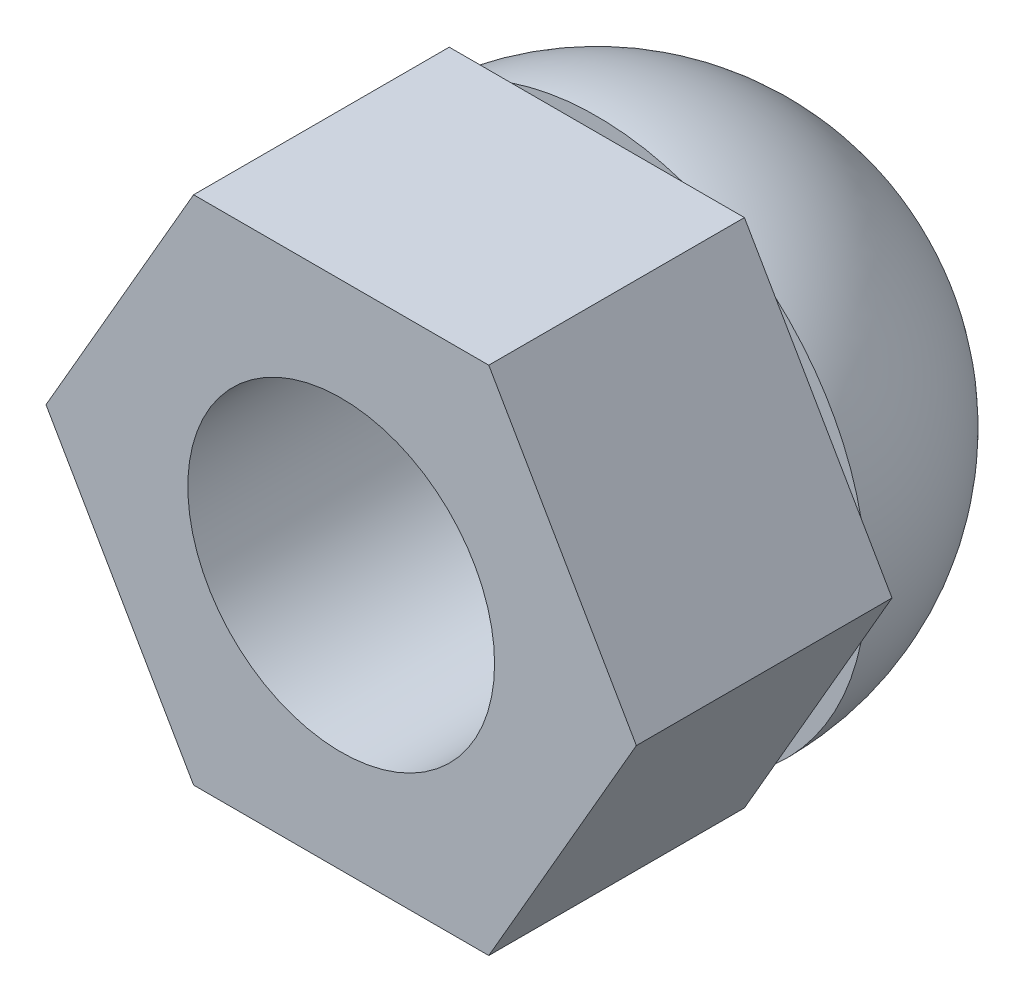
SolidWorks part; units mm, degrees
ref_plane "Plano frontal" through (0, 0, 0) normal (0, 0, 1) x (1, 0, 0)
ref_plane "Plano superior" through (0, 0, 0) normal (0, 1, 0) x (1, 0, 0)
ref_plane "Plano direito" through (0, 0, 0) normal (1, 0, 0) x (0, 0, -1)
sketch "Esboço1" plane through (0, 0, 0) normal (0, 0, 1) x (1, 0, 0)
  line L1 (2.8868, 5) -> (-2.8868, 5)
  line L2 (-2.8868, 5) -> (-5.7735, 0)
  line L3 (-5.7735, 0) -> (-2.8868, -5)
  line L4 (-2.8868, -5) -> (2.8868, -5)
  line L5 (2.8868, -5) -> (5.7735, 0)
  line L6 (5.7735, 0) -> (2.8868, 5)
  circle A0 centre (0, 0) radius 5 construction
  circle A1 centre (0, 0) radius 3
  dimension "D1" = 6
  dimension "D2" = 10
extrude "Ressalto-extrusão1" add sketch "Esboço1" along normal blind 5
sketch "Esboço2" plane through (0, 0, 0) normal (0, 1, 0) x (1, 0, 0)
  line L0 (0, 0) -> (5.2735, 0)
  line L1 (0, 5.2735) -> (0, 0)
  arc A0 (5.2735, 0) -> (0, 5.2735) centre (0, 0) ccw
  point P4 (0, 0)
  dimension "D1" = 0.5
revolve "Revolução1" add sketch "Esboço2" angle 360 about L1
